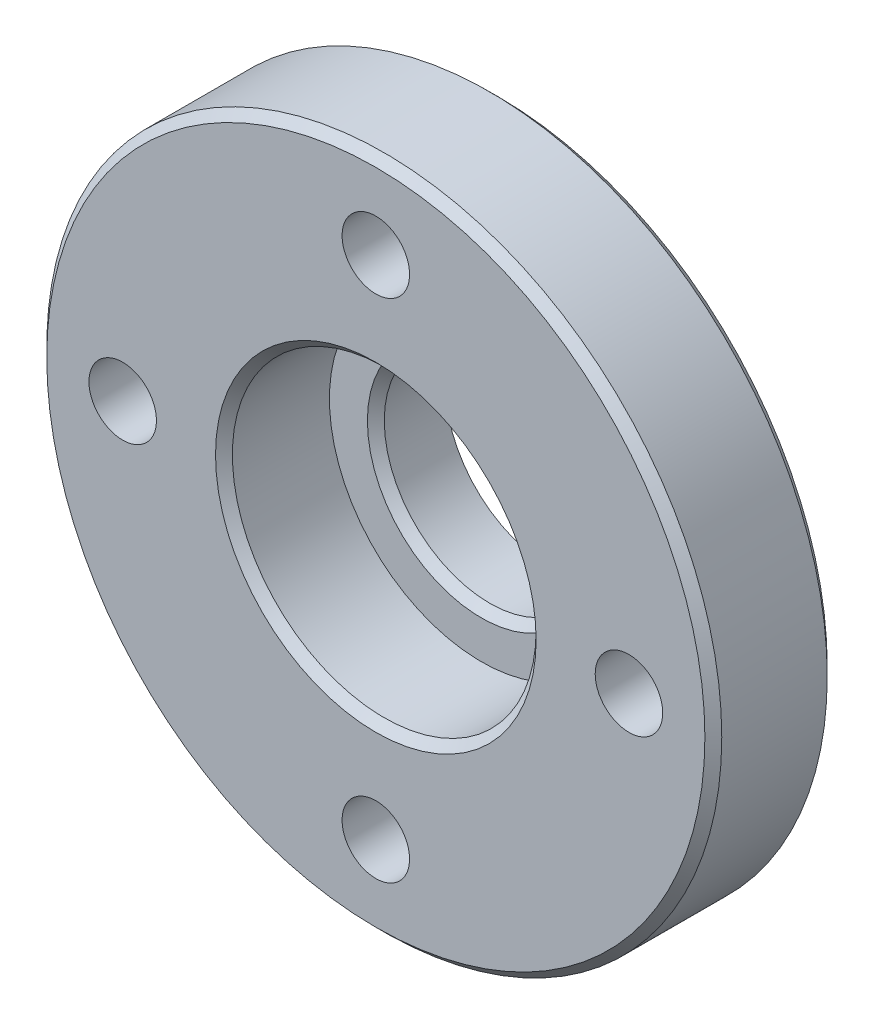
SolidWorks part; units mm, degrees
ref_plane "Front Plane" through (0, 0, 0) normal (0, 0, 1) x (1, 0, 0)
ref_plane "Top Plane" through (0, 0, 0) normal (0, 1, 0) x (1, 0, 0)
ref_plane "Right Plane" through (0, 0, 0) normal (1, 0, 0) x (0, 0, -1)
sketch "Sketch1" plane through (0, 0, 0) normal (0, 1, 0) x (1, 0, 0)
  line L0 (8, 0) -> (0, 0)
  line L1 (0, 0) -> (0, -2.9)
  line L2 (0, -2.9) -> (8, -2.9)
  line L3 (8, -2.9) -> (8, 0)
  line L4 (0, 0) -> (0, -2.9) construction
revolve "Revolve1" add sketch "Sketch1" angle 360 about L4
sketch "Sketch2" plane through (0, 0, 0) normal (0, 0, -1) x (-1, 0, 0)
  circle A0 centre (0, 0) radius 3.25
extrude "Boss-Extrude1" add sketch "Sketch2" along normal blind 1.25
hole_wizard "Ø1.6 (1.6) Diameter Hole1" positions "Sketch4" profile "Sketch3" hole size "Ø1.6" standard "ANSI Metric"
sketch "Sketch4" plane through (0, 0, 0) normal (0, 0, -1) x (-1, 0, 0)
  point P0 (0, 6)
  point P1 (6, 0)
  point P2 (0, -6)
  point P3 (-6, 0)
sketch "Sketch3" plane through (0, 6, 0) normal (1, 0, 0) x (0, 1, 0)
  line L0 (0, 0) -> (0, 2.9)
  line L1 (0, 2.9) -> (0.8, 2.9)
  line L2 (0.8, 2.9) -> (0.8, 0)
  line L5 (0.8, 0) -> (0, 0)
  line L11 (0, -6.35) -> (0, 107.95) construction
  dimension "Thru Hole Dia." = 1.6
  dimension "Thru Hole Depth" = 2.9
hole_wizard "Hole1" positions "Sketch6" profile "Sketch5" legacy
sketch "Sketch6" plane through (0, 0, 2.9) normal (0, 0, 1) x (1, 0, 0)
  point P0 (0, 0)
sketch "Sketch5" plane through (0, 0, 2.9) normal (1, 0, 0) x (0, -1, 0)
  line L0 (0, 0) -> (0, 4.15)
  line L1 (0, 4.15) -> (2.5, 4.15)
  line L2 (2.5, 4.15) -> (2.5, 2.5)
  line L3 (2.5, 2.5) -> (3.6, 2.5)
  line L4 (3.6, 2.5) -> (3.6, 0)
  line L5 (3.6, 0) -> (0, 0)
  line L6 (0, 110) -> (0, -10) construction
  dimension "Diameter" = 5
  dimension "Depth" = 4.15
  dimension "C-Bore Diameter" = 7.2
  dimension "C-Bore Depth" = 2.5
chamfer "Chamfer1" distance 0.2 angle 45 4 edges at (2.5, 0, 0.4) (8, 0, 0) (8, 0, 2.9) (3.6, 0, 2.9)
fillet "Fillet1" radius 0.3 1 edges at (-3.25, 0, 0)
